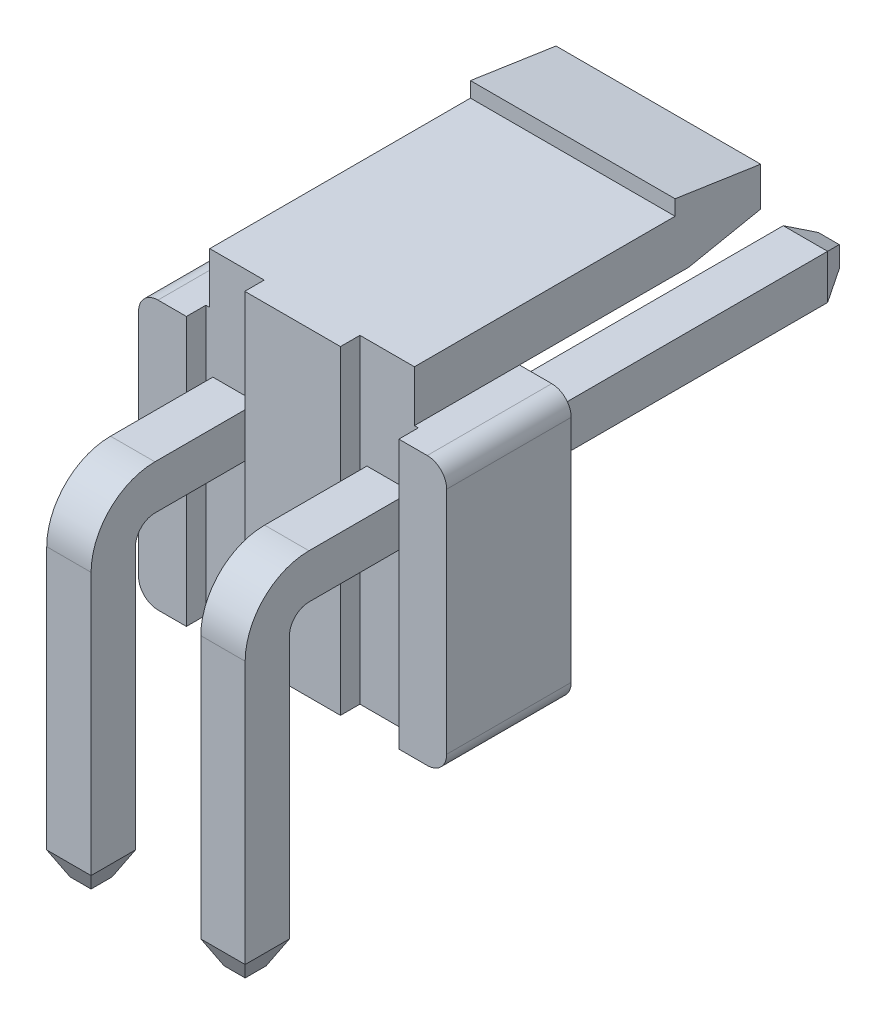
SolidWorks part; units mm, degrees
ref_plane "Front Plane" through (0, 0, 0) normal (0, 0, 1) x (1, 0, 0)
ref_plane "Top Plane" through (0, 0, 0) normal (0, 1, 0) x (1, 0, 0)
ref_plane "Right Plane" through (0, 0, 0) normal (1, 0, 0) x (0, 0, -1)
ref_plane "Plane1" through (1.98, 0, 0) normal (1, 0, 0) x (0, 0, -1)
sketch "Sketch2" plane through (1.98, 0, 0) normal (1, 0, 0) x (0, 0, -1)
  line L0 (-3.2, -3.6) -> (-3.2, 3.75) construction
  line L1 (-2.13, 4.82) -> (11.8, 4.82) construction
  line L2 (-2.63, -3.6) -> (-2.63, 3.75)
  line L3 (-2.13, 4.25) -> (11.8, 4.25)
  line L4 (-3.77, -3.6) -> (-3.77, 3.75)
  line L5 (-2.13, 5.39) -> (11.8, 5.39)
  line L6 (-2.63, -3.6) -> (-3.77, -3.6)
  line L7 (11.8, 4.25) -> (11.8, 5.39)
  line L8 (-2.13, 4.82) -> (11.8, 4.82) construction
  arc A0 (-3.2, 3.75) -> (-2.13, 4.82) centre (-2.13, 3.75) cw construction
  arc A1 (-2.63, 3.75) -> (-2.13, 4.25) centre (-2.13, 3.75) cw
  arc A2 (-3.77, 3.75) -> (-2.13, 5.39) centre (-2.13, 3.75) cw
  point P16 (6.9516, 4.82)
  point P18 (11.8, 4.82)
  dimension "D3" = 1.07
  dimension "D1" = 1.14
  dimension "D2" = 3.6
  dimension "D4" = 15
  dimension "D5" = 4.82
  dimension "D6" = 11.8
extrude "Boss-Extrude1" add sketch "Sketch2" along normal mid plane 1.14
chamfer "Chamfer1" distance 0.6 distance2 0.3 8 edges at (1.98, -3.6, 3.77) (2.55, -3.6, 3.2) (1.98, -3.6, 2.63) (1.41, -3.6, 3.2) (1.98, 4.25, -11.8) (2.55, 4.82, -11.8) (1.98, 5.39, -11.8) (1.41, 4.82, -11.8)
mirror "Mirror2" about plane through (0, 0, 0) normal (1, 0, 0) of bodies 101
sketch "Sketch3" plane through (0, 0, 0) normal (0, 0, 1) x (1, 0, 0)
  line L0 (0, -1000) -> (0, 49000) construction
  line L1 (-3.46, 6.9) -> (3.46, 6.9)
  line L2 (-3.96, 6.4) -> (-3.96, 0.5)
  line L3 (-3.46, 0) -> (3.46, 0)
  line L4 (3.96, 6.4) -> (3.96, 0.5)
  line L5 (-3.96, 6.9) -> (3.96, 0) construction
  line L6 (-3.96, 0) -> (3.96, 6.9) construction
  line L7 (-2.55, 4.25) -> (-2.55, 5.39) construction
  line L8 (-2.55, 5.39) -> (-1.41, 5.39) construction
  line L9 (-1.41, 5.39) -> (-1.41, 4.25) construction
  line L10 (-1.41, 4.25) -> (-2.55, 4.25) construction
  line L11 (1.41, 4.25) -> (2.55, 4.25) construction
  line L12 (2.55, 4.25) -> (2.55, 5.39) construction
  line L13 (2.55, 5.39) -> (1.41, 5.39) construction
  line L14 (1.41, 5.39) -> (1.41, 4.25) construction
  line L15 (-2.55, 4.25) -> (-2.55, 5.39)
  line L16 (-2.55, 5.39) -> (-1.41, 5.39)
  line L17 (-1.41, 5.39) -> (-1.41, 4.25)
  line L18 (-1.41, 4.25) -> (-2.55, 4.25)
  line L19 (1.41, 4.25) -> (2.55, 4.25)
  line L20 (2.55, 4.25) -> (2.55, 5.39)
  line L21 (2.55, 5.39) -> (1.41, 5.39)
  line L22 (1.41, 5.39) -> (1.41, 4.25)
  arc A0 (-3.96, 0.5) -> (-3.46, 0) centre (-3.46, 0.5) ccw
  arc A1 (3.46, 0) -> (3.96, 0.5) centre (3.46, 0.5) ccw
  arc A2 (3.46, 6.9) -> (3.96, 6.4) centre (3.46, 6.4) cw
  arc A3 (-3.46, 6.9) -> (-3.96, 6.4) centre (-3.46, 6.4) ccw
  point P0 (0, 3.45)
  dimension "D1" = 0.5
  dimension "D2" = 6.9
  dimension "D3" = 7.92
extrude "Boss-Extrude2" add sketch "Sketch3" against normal blind 3.2 separate body
sketch "Sketch6" plane through (0, 0, 0) normal (1, 0, 0) x (0, 0, -1)
  line L0 (0, 6.9) -> (0, 8.21)
  line L1 (0, 8.21) -> (7.2, 8.21)
  line L2 (7.2, 8.21) -> (7.2, 8.6)
  line L3 (7.2, 8.6) -> (9.4, 8.27)
  line L4 (9.4, 8.27) -> (9.4, 7.27)
  line L5 (9.4, 7.27) -> (7.55, 6.9)
  line L6 (7.55, 6.9) -> (0, 6.9)
  point P3 (7.8, 8.27)
  point P9 (3.2, 6.9)
  point P10 (0, 0)
  point P11 (0.2902, 7.81)
  dimension "D1" = 9.4
  dimension "D2" = 0.39
  dimension "D3" = 0.37
  dimension "D4" = 1
  dimension "D5" = 7.2
  dimension "D6" = 1.85
  dimension "D7" = 1.31
extrude "Boss-Extrude3" add sketch "Sketch6" along normal mid plane 5.26
sketch "Sketch4" plane through (0, 0, 0) normal (0, 1, 0) x (1, 0, 0)
  line L5 (0, -1000) -> (0, 49000) construction
  line L11 (2.63, 0) -> (-2.63, 0) construction
  line L12 (-2.73, 0) -> (-1.23, 0)
  line L13 (-2.73, 0) -> (-2.73, 0.5)
  line L14 (-2.73, 0.5) -> (-1.23, 0.5)
  line L15 (-1.23, 0) -> (-1.23, 0.5)
  line L16 (-2.55, -2.13) -> (-1.41, -2.13) construction
  line L17 (1.23, 0) -> (1.23, 0.5)
  line L18 (2.73, 0.5) -> (1.23, 0.5)
  line L19 (2.73, 0) -> (2.73, 0.5)
  line L20 (2.73, 0) -> (1.23, 0)
  point P11 (-1.98, -2.13)
  point P12 (-1.98, 0)
  dimension "D1" = 1.5
  dimension "D2" = 0.5
extrude "Cut-Extrude1" cut sketch "Sketch4" against normal through all both and the other way through all
